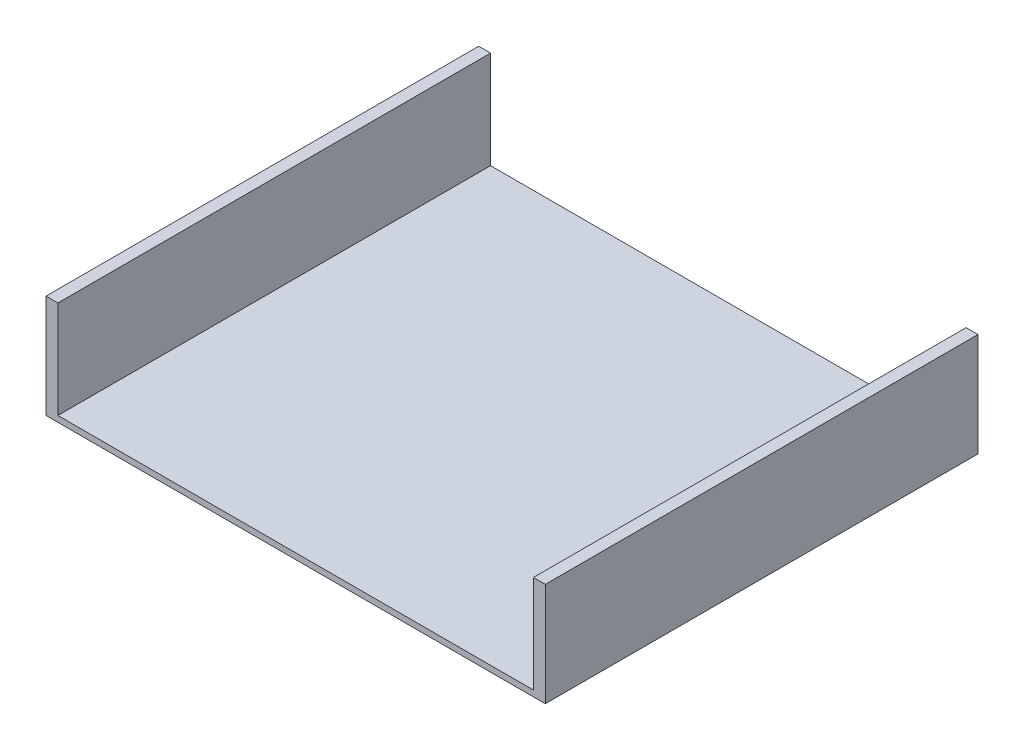
SolidWorks part; units mm, degrees
ref_plane "Front" through (0, 0, 0) normal (0, 0, 1) x (1, 0, 0)
ref_plane "Top" through (0, 0, 0) normal (0, 1, 0) x (1, 0, 0)
ref_plane "Right" through (0, 0, 0) normal (1, 0, 0) x (0, 0, -1)
sketch "草图1" plane through (0, 0, 0) normal (0, 0, 1) x (1, 0, 0)
  line L0 (-100, 20.5) -> (-105, 20.5)
  line L1 (-100, -20.5) -> (100, -20.5)
  line L2 (-100, -20.5) -> (-100, 20.5)
  line L3 (-100, 20.5) -> (100, 20.5)
  line L4 (100, -20.5) -> (100, 20.5)
  line L5 (-100, -20.5) -> (100, 20.5) construction
  line L6 (-100, 20.5) -> (100, -20.5) construction
  line L7 (-105, -23) -> (105, -23)
  line L8 (-105, -23) -> (-105, 23)
  line L9 (-105, 23) -> (105, 23)
  line L10 (105, -23) -> (105, 23)
  line L11 (-105, -23) -> (105, 23) construction
  line L12 (-105, 23) -> (105, -23) construction
  line L13 (-105, 20.5) -> (100, 20.5)
  line L14 (105, 20.5) -> (100, 20.5)
  point P0 (0, 0)
  point P6 (0, 0)
  point P13 (0, 0)
  point P14 (0, 0)
  dimension "D1" = 210
  dimension "D2" = 200
  dimension "D3" = 41
  dimension "D4" = 46
extrude "凸台-拉伸1" add sketch "草图1" along normal blind 182 contours L10 L14 L4 L1 L2 L0 L8 L7
